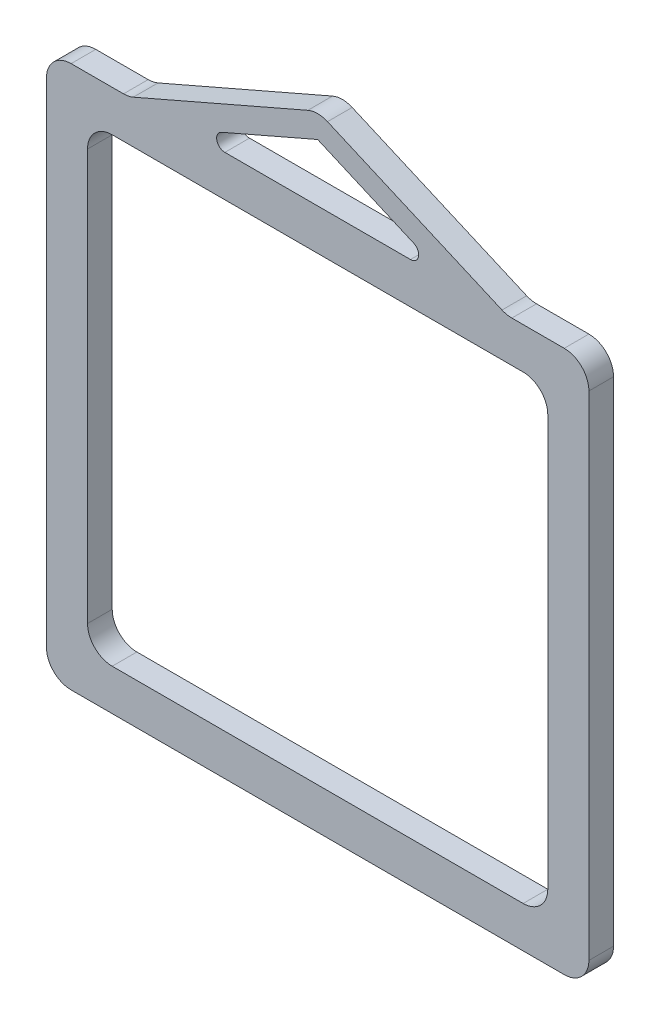
SolidWorks part; units mm, degrees
ref_plane "Front Plane" through (0, 0, 0) normal (0, 0, 1) x (1, 0, 0)
ref_plane "Top Plane" through (0, 0, 0) normal (0, 1, 0) x (1, 0, 0)
ref_plane "Right Plane" through (0, 0, 0) normal (1, 0, 0) x (0, 0, -1)
sketch "Sketch1" plane through (0, 0, 0) normal (0, 0, 1) x (1, 0, 0)
  line L0 (-23, 33) -> (0, 43)
  line L1 (-28, 28) -> (28, 28)
  line L2 (-28, 28) -> (-28, -28)
  line L3 (-28, -28) -> (28, -28)
  line L4 (28, 28) -> (28, -28)
  line L5 (-28, 28) -> (28, -28) construction
  line L6 (-28, -28) -> (28, 28) construction
  line L7 (-33, 33) -> (-23, 33)
  line L8 (-33, 33) -> (-33, -33)
  line L9 (-33, -33) -> (33, -33)
  line L10 (33, 33) -> (33, -33)
  line L11 (-33, 33) -> (33, -33) construction
  line L12 (-33, -33) -> (33, 33) construction
  line L13 (0, 43) -> (23, 33)
  line L14 (-16.1, 33) -> (0, 40)
  line L15 (0, 40) -> (16.1, 33)
  line L16 (-16.1, 33) -> (16.1, 33)
  line L17 (23, 33) -> (33, 33)
  point P0 (0, 0)
  point P6 (0, 0)
  dimension "D1" = 56
  dimension "D2" = 56
  dimension "D3" = 5
  dimension "D4" = 5
  dimension "D5" = 10
  dimension "D6" = 10
  dimension "D7" = 10
  dimension "D8" = 7
extrude "Boss-Extrude1" add sketch "Sketch1" along normal blind 3
fillet "Fillet1" radius 3 11 edges at (-23, 33, 1.5) (-28, -28, 1.5) (28, -28, 1.5) (33, -33, 1.5) (-33, -33, 1.5) (28, 28, 1.5) (23, 33, 1.5) (0, 43, 1.5) (33, 33, 1.5) (-28, 28, 1.5) (-33, 33, 1.5)
fillet "Fillet2" radius 1 2 edges at (-16.1, 33, 1.5) (16.1, 33, 1.5)
